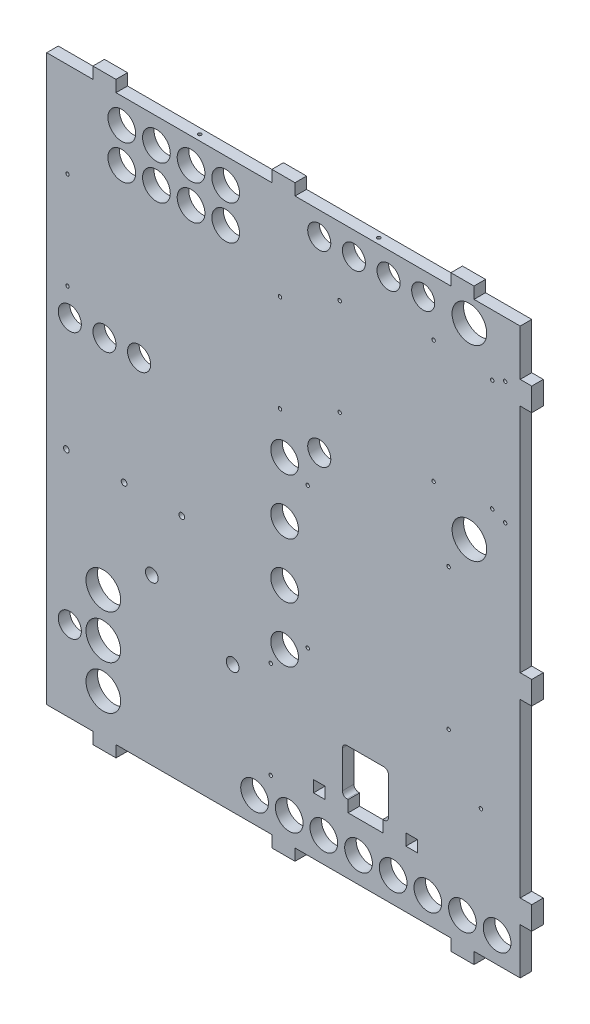
SolidWorks part; units mm, degrees
ref_plane "Ebene vorne" through (0, 0, 0) normal (0, 0, 1) x (1, 0, 0)
ref_plane "Ebene oben" through (0, 0, 0) normal (0, 1, 0) x (1, 0, 0)
ref_plane "Ebene rechts" through (0, 0, 0) normal (1, 0, 0) x (0, 0, -1)
sketch "Skizze1" plane through (0, 0, 0) normal (0, 0, 1) x (1, 0, 0)
  line L0 (0, 0) -> (0, -83406.5938) construction
  line L1 (0, 0) -> (83406.5938, 0) construction
  line L2 (55, 67.225) -> (75, 67.225)
  line L3 (-100, -67.225) -> (100, -67.225)
  line L4 (10.5, -37.555) -> (10.5, -42.555)
  line L5 (-100, 67.225) -> (-85, 67.225)
  line L6 (50.5, -37.555) -> (55.5, -37.555)
  line L7 (-100, -67.225) -> (100, 67.225) construction
  line L8 (-100, 67.225) -> (100, -67.225) construction
  line L9 (100, 47.225) -> (100, 67.225)
  line L10 (75, 67.225) -> (75, 72.225)
  line L11 (75, 72.225) -> (85, 72.225)
  line L12 (85, 67.225) -> (85, 72.225)
  line L13 (85, 67.225) -> (100, 67.225)
  line L14 (45, 67.225) -> (45, 72.225)
  line L15 (45, 72.225) -> (55, 72.225)
  line L16 (55, 67.225) -> (55, 72.225)
  line L17 (50.5, -37.555) -> (50.5, -42.555)
  line L18 (50.5, -42.555) -> (55.5, -42.555)
  line L19 (55.5, -37.555) -> (55.5, -42.555)
  line L20 (15.5, -42.555) -> (10.5, -42.555)
  line L21 (100, 47.225) -> (105, 47.225)
  line L22 (15.5, -37.555) -> (15.5, -42.555)
  line L23 (100, 37.225) -> (105, 37.225)
  line L24 (105, 47.225) -> (105, 37.225)
  line L25 (15.5, -37.555) -> (10.5, -37.555)
  line L26 (-75, 67.225) -> (45, 67.225)
  line L27 (100, -47.225) -> (100, -67.225)
  line L29 (-75, 67.225) -> (-75, 72.225)
  line L30 (-75, 72.225) -> (-85, 72.225)
  line L31 (105, -47.225) -> (105, -37.225)
  line L32 (100, -37.225) -> (105, -37.225)
  line L33 (-85, 67.225) -> (-85, 72.225)
  line L34 (100, -47.225) -> (105, -47.225)
  line L38 (100, 37.225) -> (100, -37.225)
  line L44 (-100, 37.225) -> (-100, -37.225)
  line L48 (-100, -47.225) -> (-105, -47.225)
  line L50 (-100, -37.225) -> (-105, -37.225)
  line L51 (-105, -47.225) -> (-105, -37.225)
  line L53 (-100, -47.225) -> (-100, -67.225)
  line L55 (-105, 47.225) -> (-105, 37.225)
  line L56 (-100, 37.225) -> (-105, 37.225)
  line L58 (-100, 47.225) -> (-105, 47.225)
  line L62 (-100, 47.225) -> (-100, 67.225)
  line L63 (33, -37.555) -> (33, -42.555) construction
  line L64 (25.5, -37.555) -> (40.5, -37.555)
  line L65 (25.5, -37.555) -> (25.5, -42.555)
  line L66 (25.5, -42.555) -> (40.5, -42.555)
  line L67 (40.5, -37.555) -> (40.5, -42.555)
  line L68 (105, 0) -> (105, -50000) construction
  point P5 (0, 0)
  dimension "D1" = 134.45
  dimension "D2" = 200
  dimension "D3" = 10
  dimension "D4" = 20
  dimension "D5" = 5
  dimension "D6" = 20
  dimension "D7" = 20
  dimension "D8" = 29.67
  dimension "D9" = 72
  dimension "D10" = 15
  dimension "D11" = 105
  dimension "D12" = 10
  dimension "D13" = 5
  dimension "D14" = 15
extrude "Aufsatz-Linear austragen1" add sketch "Skizze1" along normal blind 5
sketch "Skizze2" plane through (0, 0, 5) normal (0, 0, 1) x (1, 0, 0)
  line L0 (-42, 48.7841) -> (-42, -49951.2159) construction
  line L1 (-80.5107, -3.925) -> (49919.4893, -3.925) construction
  line L2 (-100, 67.225) -> (-85, 67.225) construction
  line L4 (100, 37.225) -> (100, -37.225) construction
  circle A0 centre (-59.5, 4.075) radius 2.75
  circle A1 centre (-24.5, 4.075) radius 2.75 construction
  circle A2 centre (-59.5, -11.925) radius 2.75 construction
  circle A3 centre (-24.5, -11.925) radius 2.75
  dimension "D1" = 5.5
  dimension "D2" = 63.15
  dimension "D3" = 142
  dimension "D4" = 35
  dimension "D5" = 16
extrude "Schnitt-Linear austragen1" cut sketch "Skizze2" against normal through all
sketch "Skizze3" plane through (0, 0, 5) normal (0, 0, 1) x (1, 0, 0)
  line L0 (33, -42.555) -> (33, -17.555) construction
  line L1 (25, -17.555) -> (41, -17.555)
  line L2 (23, -19.555) -> (23, -35.555)
  line L3 (37, -37.555) -> (41, -37.555)
  line L4 (43, -19.555) -> (43, -35.555)
  line L5 (-14.5, -32.225) -> (4.5, -32.225) construction
  line L6 (-17.5, -35.225) -> (-17.5, -54.225) construction
  line L7 (-14.5, -57.225) -> (4.5, -57.225) construction
  line L8 (7.5, -35.225) -> (7.5, -54.225) construction
  line L9 (25.5, -42.555) -> (40.5, -42.555) construction
  line L10 (25.5, -37.555) -> (40.5, -37.555) construction
  line L11 (29, -37.555) -> (25, -37.555)
  line L12 (-66.5, 54.225) -> (-66.5, 35.225)
  line L13 (37, -37.555) -> (29, -37.555)
  line L14 (-5, -32.225) -> (-5, -50032.225) construction
  line L17 (-88.5, 32.225) -> (-69.5, 32.225)
  line L18 (-100, -67.225) -> (100, -67.225) construction
  line L19 (-5, 57.225) -> (49995, 57.225) construction
  line L20 (-100, 67.225) -> (-85, 67.225) construction
  line L21 (-42, 57.225) -> (-42, -49942.775) construction
  line L24 (4.5, 57.225) -> (-14.5, 57.225)
  line L25 (7.5, 54.225) -> (7.5, 35.225)
  line L26 (4.5, 32.225) -> (-14.5, 32.225)
  line L27 (-17.5, 54.225) -> (-17.5, 35.225)
  line L28 (-91.5, 54.225) -> (-91.5, 35.225)
  line L29 (-88.5, 57.225) -> (-69.5, 57.225)
  line L30 (-79, 57.225) -> (-79, -49942.775) construction
  line L31 (-5, 22.3625) -> (49995, 22.3625) construction
  line L32 (4.5, -12.5) -> (-14.5, -12.5) construction
  line L33 (-17.5, -9.5) -> (-17.5, 9.5) construction
  line L34 (4.5, 12.5) -> (-14.5, 12.5) construction
  line L35 (7.5, -9.5) -> (7.5, 9.5) construction
  line L36 (4.5, 32.225) -> (4.5, 12.5) construction
  line L37 (4.5, -12.5) -> (4.5, -32.225) construction
  line L38 (4.5, -32.225) -> (4.5, -12.5) construction
  circle A0 centre (-24.5, -11.925) radius 2.75 construction
  arc A1 (23, -35.555) -> (25, -37.555) centre (25, -35.555) ccw
  arc A2 (43, -35.555) -> (41, -37.555) centre (41, -35.555) cw
  arc A3 (43, -19.555) -> (41, -17.555) centre (41, -19.555) ccw
  arc A4 (25, -17.555) -> (23, -19.555) centre (25, -19.555) ccw
  arc A5 (-17.5, -54.225) -> (-14.5, -57.225) centre (-14.5, -54.225) ccw construction
  arc A6 (7.5, -54.225) -> (4.5, -57.225) centre (4.5, -54.225) cw construction
  arc A8 (7.5, -35.225) -> (4.5, -32.225) centre (4.5, -35.225) ccw construction
  arc A9 (-14.5, -32.225) -> (-17.5, -35.225) centre (-14.5, -35.225) ccw construction
  arc A10 (7.5, 35.225) -> (4.5, 32.225) centre (4.5, 35.225) cw
  arc A11 (-14.5, 32.225) -> (-17.5, 35.225) centre (-14.5, 35.225) cw
  arc A12 (-17.5, 54.225) -> (-14.5, 57.225) centre (-14.5, 54.225) cw
  arc A14 (4.5, 57.225) -> (7.5, 54.225) centre (4.5, 54.225) cw
  arc A15 (-88.5, 57.225) -> (-91.5, 54.225) centre (-88.5, 54.225) ccw
  arc A16 (-66.5, 54.225) -> (-69.5, 57.225) centre (-69.5, 54.225) ccw
  arc A17 (-69.5, 32.225) -> (-66.5, 35.225) centre (-69.5, 35.225) ccw
  arc A18 (-91.5, 35.225) -> (-88.5, 32.225) centre (-88.5, 35.225) ccw
  circle A19 centre (-59.5, 4.075) radius 2.75 construction
  arc A20 (-17.5, -9.5) -> (-14.5, -12.5) centre (-14.5, -9.5) ccw construction
  arc A21 (-14.5, 12.5) -> (-17.5, 9.5) centre (-14.5, 9.5) ccw construction
  arc A22 (7.5, 9.5) -> (4.5, 12.5) centre (4.5, 9.5) ccw construction
  arc A23 (4.5, -12.5) -> (7.5, -9.5) centre (4.5, -9.5) ccw construction
  point P19 (23, -37.555)
  point P22 (43, -37.555)
  point P25 (43, -17.555)
  point P28 (23, -17.555)
  point P52 (43, -37.555)
  point P53 (-5, -32.225)
  point P67 (-17.5, 32.225)
  point P70 (-17.5, 57.225)
  point P73 (7.5, 57.225)
  point P86 (-91.5, 57.225)
  point P87 (-66.5, 57.225)
  point P88 (-66.5, 32.225)
  point P91 (-79, 57.225)
  dimension "D1" = 20
  dimension "D2" = 20
  dimension "D6" = 25
  dimension "D3" = 2
  dimension "D7" = 3
  dimension "D12" = 25
  dimension "D5" = 19.5
  dimension "D15" = 2
  dimension "D17" = 3
  dimension "D18" = 19.5
  dimension "D4" = 10
  dimension "D8" = 25
  dimension "D9" = 25
  dimension "D11" = 10
  dimension "D13" = 0
  dimension "D14" = 8
extrude "Schnitt-Linear austragen2" cut sketch "Skizze3" against normal through all
sketch "Skizze4" plane through (0, 0, 5) normal (0, 0, 1) x (1, 0, 0)
  line L0 (55, 67.225) -> (75, 67.225) construction
  line L1 (100, 47.225) -> (100, 67.225) construction
  line L2 (-100, -67.225) -> (100, -67.225) construction
  line L3 (-80.5, -30.925) -> (49919.5, -30.925) construction
  line L4 (-80.5, -30.925) -> (-80.5, -50030.925) construction
  circle A0 centre (45.5, 53.325) radius 7.5 construction
  circle A1 centre (-80.5, -30.925) radius 7.5
  circle A2 centre (-59.5, 4.075) radius 2.75 construction
  circle A3 centre (-80.5, -11.925) radius 7.5
  circle A4 centre (-80.5, -49.925) radius 7.5
  dimension "D1" = 13.9
  dimension "D3" = 15
  dimension "D5" = 21
  dimension "D6" = 19
  dimension "D2" = 54.5
  dimension "D4" = 36.3
extrude "Schnitt-Linear austragen3" cut sketch "Skizze4" against normal through all
sketch "Skizze5" plane through (0, 0, 5) normal (0, 0, 1) x (1, 0, 0)
  line L0 (-8, -45.225) -> (-8, -3.225) construction
  line L1 (83, -12.225) -> (-8, -12.225) construction
  line L2 (-100, -67.225) -> (100, -67.225) construction
  line L3 (100, 37.225) -> (100, -37.225) construction
  line L4 (-30.2483, -49.225) -> (49969.7517, -49.225) construction
  line L5 (-17.9531, -56.225) -> (49982.0469, -56.225) construction
  line L6 (22.5, -56.9878) -> (22.5, -50056.9878) construction
  line L7 (37.5, -10.225) -> (37.5, -50010.225) construction
  circle A0 centre (-8, -45.225) radius 0.75
  circle A1 centre (-8, -3.225) radius 0.75
  circle A2 centre (83, -12.225) radius 0.75
  circle A3 centre (-15, -56.225) radius 6
  circle A4 centre (0, -56.225) radius 6
  circle A5 centre (15, -56.225) radius 6
  circle A6 centre (30, -56.225) radius 6
  circle A7 centre (45, -56.225) radius 6
  circle A8 centre (60, -56.225) radius 6
  circle A9 centre (75, -56.225) radius 6
  circle A10 centre (90, -56.225) radius 6
  point P33 (0, 0)
  point P36 (37.5, -12.225)
  dimension "D1" = 1.5
  dimension "D9" = 12
  dimension "D2" = 42
  dimension "D4" = 91
  dimension "D3" = 9
  dimension "D5" = 22
  dimension "D6" = 17
  dimension "D7" = 4
  dimension "D10" = 7
  dimension "D11" = 15
  dimension "D8" = 8
extrude "Sensors" cut sketch "Skizze5" against normal through all
sketch "Skizze6" plane through (0, 0, 0) normal (0, 0, -1) x (-1, 0, 0)
  line L0 (100, -67.225) -> (-100, -67.225) construction
  line L1 (160, 47.225) -> (160, 37.225)
  line L2 (100, 67.225) -> (100, -67.225)
  line L3 (100, -67.225) -> (160, -67.225)
  line L4 (160, 67.225) -> (160, 47.225)
  line L6 (100, -37.225) -> (105, -37.225) construction
  line L7 (160, -47.225) -> (160, -67.225)
  line L8 (100, -47.225) -> (105, -47.225) construction
  line L9 (100, 47.225) -> (105, 47.225) construction
  line L10 (100, 37.225) -> (105, 37.225) construction
  line L11 (75, 67.225) -> (-45, 67.225) construction
  line L17 (160, 37.225) -> (160, -37.225)
  line L18 (-30.5, 67.225) -> (100, 67.225)
  line L19 (-30.5, 67.225) -> (-30.5, 177.225)
  line L20 (-30.5, 177.225) -> (160, 177.225)
  line L21 (160, 67.225) -> (160, 177.225)
  line L22 (-100, 47.225) -> (-100, 67.225) construction
  line L23 (160, -37.225) -> (160, -47.225)
  dimension "D1" = 60
  dimension "D2" = 110
  dimension "D3" = 69.5
extrude "Aufsatz-Linear austragen2" add sketch "Skizze6" against normal blind 5
sketch "Skizze7" plane through (0, 0, 0) normal (0, 0, -1) x (-1, 0, 0)
  line L0 (71.5, 32.775) -> (96.5, 32.775) construction
  line L1 (160, -67.225) -> (-100, -67.225) construction
  line L4 (91.5, 54.225) -> (91.5, 35.225) construction
  line L5 (46.5, 32.775) -> (71.5, 32.775) construction
  line L6 (122.7956, 60.525) -> (50122.7956, 60.525) construction
  circle A0 centre (71.5, 32.775) radius 1.25
  circle A1 centre (96.5, 32.775) radius 1.25
  circle A4 centre (46.5, 32.775) radius 1.25
  dimension "D3" = 2.5
  dimension "D1" = 100
  dimension "D2" = 25
  dimension "D4" = 20
extrude "Schnitt-Linear austragen5" cut sketch "Skizze7" against normal through all
sketch "Sketch1" plane through (0, 0, 5) normal (0, 0, 1) x (1, 0, 0)
  line L1 (30.5, 177.225) -> (100, 177.225)
  line L2 (30.5, 177.225) -> (30.5, 67.225)
  line L3 (30.5, 67.225) -> (100, 67.225)
  line L4 (100, 177.225) -> (100, 67.225)
extrude "Boss-Extrude1" add sketch "Sketch1" against normal blind 5
sketch "Skizze9" plane through (0, 0, 5) normal (0, 0, 1) x (1, 0, 0)
  line L0 (-33.1526, 41.015) -> (49966.8474, 41.015) construction
  line L1 (38.5, 36.3664) -> (38.5, 48631.464) construction
  line L5 (-2, 7.1234) -> (-2, 89.5656) construction
  line L7 (-17.5, 54.225) -> (-17.5, 35.225) construction
  line L8 (4.5, 57.225) -> (-14.5, 57.225) construction
  circle A0 centre (8, 71.515) radius 0.75
  circle A1 centre (69, 71.515) radius 0.75
  circle A2 centre (8, 10.515) radius 0.75
  circle A3 centre (69, 10.515) radius 0.75
  circle A4 centre (-2, 5.015) radius 6
  circle A5 centre (-2, 29.015) radius 6
  circle A6 centre (-2, 53.015) radius 6
  circle A7 centre (-2, 77.015) radius 6
  point P13 (0, 0)
  point P16 (0, 0)
  point P29 (0, 0)
  dimension "D1" = 1.5
  dimension "D8" = 12
  dimension "D2" = 61
  dimension "D3" = 61
  dimension "D7" = 24
  dimension "D5" = 15.5
  dimension "D9" = 4.21
  dimension "D4" = 10
  dimension "D6" = 4
extrude "DiscreteChannel" cut sketch "Skizze9" against normal through all
sketch "Skizze10" plane through (0, 0, 5) normal (0, 0, 1) x (1, 0, 0)
  line L0 (-50, 127.2474) -> (-50, -49872.7526) construction
  line L1 (-69.94, 115.225) -> (49930.06, 115.225) construction
  line L4 (-50.8687, 166.225) -> (49949.1313, 166.225) construction
  line L5 (-75.5, 136.225) -> (49924.5, 136.225) construction
  line L6 (-72.5, 172.225) -> (-27.5, 172.225) construction
  line L7 (-72.5, 166.225) -> (-72.5, 151.225) construction
  line L8 (-160, 177.225) -> (100, 177.225) construction
  line L9 (100, 47.225) -> (100, 177.225) construction
  circle A0 centre (-4, 136.225) radius 0.75
  circle A1 centre (-4, 94.225) radius 0.75
  circle A2 centre (-96, 136.225) radius 0.75
  circle A3 centre (-96, 94.225) radius 0.75
  circle A4 centre (-72.5, 166.225) radius 6
  circle A5 centre (-2, 5.015) radius 6 construction
  circle A6 centre (-57.5, 166.225) radius 6
  circle A7 centre (-42.5, 166.225) radius 6
  circle A8 centre (-27.5, 166.225) radius 6
  circle A9 centre (-27.5, 151.225) radius 6
  circle A10 centre (-42.5, 151.225) radius 6
  circle A11 centre (-57.5, 151.225) radius 6
  circle A12 centre (-72.5, 151.225) radius 6
  point P20 (-50, 172.225)
  point P29 (45.295, 151.225)
  dimension "D6" = 4
  dimension "D5" = 1.5
  dimension "D1" = 42
  dimension "D2" = 92
  dimension "D7" = 15
  dimension "D9" = 30
  dimension "D8" = 15
  dimension "D4" = 11
  dimension "D10" = 150
  dimension "D3" = 2
extrude "ContChannel" cut sketch "Skizze10" against normal through all
sketch "Sketch2" plane through (0, 0, 5) normal (0, 0, 1) x (1, 0, 0)
  line L0 (-14.5, 32.225) -> (-7.0691, 32.225) construction
  line L1 (3.0691, 32.225) -> (4.5, 32.225) construction
  line L2 (7.5, 35.225) -> (7.5, 54.225) construction
  line L3 (4.5, 57.225) -> (2.275, 57.225) construction
  line L4 (-6.275, 57.225) -> (-14.5, 57.225) construction
  line L5 (-17.5, 54.225) -> (-17.5, 35.225) construction
  line L6 (-14.5, 32.225) -> (-7.0691, 32.225)
  line L7 (3.0691, 32.225) -> (4.5, 32.225)
  line L8 (7.5, 35.225) -> (7.5, 54.225)
  line L9 (4.5, 57.225) -> (2.275, 57.225)
  line L10 (-6.275, 57.225) -> (-14.5, 57.225)
  line L11 (-17.5, 54.225) -> (-17.5, 35.225)
  arc A0 (-17.5, 35.225) -> (-14.5, 32.225) centre (-14.5, 35.225) ccw construction
  arc A1 (-7.0691, 32.225) -> (3.0691, 32.225) centre (-2, 29.015) ccw construction
  arc A2 (4.5, 32.225) -> (7.5, 35.225) centre (4.5, 35.225) ccw construction
  arc A3 (7.5, 54.225) -> (4.5, 57.225) centre (4.5, 54.225) ccw construction
  arc A4 (2.275, 57.225) -> (-6.275, 57.225) centre (-2, 53.015) ccw construction
  arc A5 (-14.5, 57.225) -> (-17.5, 54.225) centre (-14.5, 54.225) ccw construction
  arc A6 (-17.5, 35.225) -> (-14.5, 32.225) centre (-14.5, 35.225) ccw
  arc A7 (-7.0691, 32.225) -> (3.0691, 32.225) centre (-2, 29.015) ccw construction
  arc A8 (4.5, 32.225) -> (7.5, 35.225) centre (4.5, 35.225) ccw
  arc A9 (7.5, 54.225) -> (4.5, 57.225) centre (4.5, 54.225) ccw
  arc A10 (2.275, 57.225) -> (-6.275, 57.225) centre (-2, 53.015) ccw construction
  arc A11 (-14.5, 57.225) -> (-17.5, 54.225) centre (-14.5, 54.225) ccw
  arc A12 (-7.0691, 32.225) -> (3.0691, 32.225) centre (-2, 29.015) cw
  arc A13 (-6.275, 57.225) -> (2.275, 57.225) centre (-2, 53.015) ccw
  point P20 (2.6378, 56.8217)
extrude "Boss-Extrude2" add sketch "Sketch2" against normal blind 5
sketch "Skizze8" plane through (0, 0, 5) normal (0, 0, 1) x (1, 0, 0)
  line L0 (-165.5788, 126.725) -> (49834.4212, 126.725) construction
  line L1 (78, 176.1292) -> (78, 50176.1292) construction
  line L2 (-160, 177.225) -> (100, 177.225) construction
  line L3 (100, 47.225) -> (100, 177.225) construction
  line L5 (62.5, 100.225) -> (93.5, 100.225) construction
  circle A0 centre (62.5, 153.225) radius 0.75
  circle A1 centre (93.5, 153.225) radius 0.75
  circle A2 centre (62.5, 100.225) radius 0.75
  circle A3 centre (93.5, 100.225) radius 0.75
  circle A4 centre (78, 86.225) radius 7.5
  circle A5 centre (-80.5, -11.925) radius 7.5 construction
  circle A6 centre (78, 167.225) radius 7.5
  dimension "D1" = 1.5
  dimension "D2" = 53
  dimension "D3" = 31
  dimension "D4" = 14
  dimension "D5" = 10
  dimension "D6" = 6.5
extrude "StepDownConverter" cut sketch "Skizze8" against normal through all
sketch "Sketch3" plane through (0, 0, 5) normal (0, 0, 1) x (1, 0, 0)
  line L0 (46.6666, 126.725) -> (50046.6666, 126.725) construction
  line L1 (100, 47.225) -> (100, 177.225) construction
  line L2 (93.5, 153.225) -> (93.5, 100.225) construction
  line L3 (78, 167.225) -> (50078, 167.225) construction
  circle A0 centre (21.85, 147.68) radius 0.75
  circle A1 centre (87.89, 102.59) radius 0.75
  circle A2 centre (87.89, 150.86) radius 0.75
  circle A3 centre (21.85, 105.77) radius 0.75
  circle A4 centre (13, 167.225) radius 5
  circle A5 centre (28, 167.225) radius 5
  circle A6 centre (43, 167.225) radius 5
  circle A7 centre (58, 167.225) radius 5
  circle A8 centre (78, 167.225) radius 7.5 construction
  circle A9 centre (13, 86.225) radius 5
  point P10 (93.5, 126.725)
  point P28 (0, 0)
  point P29 (6.1817, 167.225)
  dimension "D4" = 1.5
  dimension "D6" = 10
  dimension "D1" = 66.04
  dimension "D2" = 41.91
  dimension "D3" = 3.18
  dimension "D5" = 12.11
  dimension "D8" = 15
  dimension "D9" = 20
  dimension "D7" = 4
extrude "BBB" cut sketch "Sketch3" against normal blind 5
sketch "Sketch4" plane through (0, 0, 5) normal (0, 0, 1) x (1, 0, 0)
  line L0 (-88.5, 32.225) -> (-72.6225, 32.225) construction
  line L1 (-70.3775, 32.225) -> (-69.5, 32.225) construction
  line L2 (-66.5, 35.225) -> (-66.5, 54.225) construction
  line L3 (-69.5, 57.225) -> (-88.5, 57.225) construction
  line L4 (-91.5, 54.225) -> (-91.5, 35.225) construction
  line L5 (-88.5, 32.225) -> (-72.6225, 32.225)
  line L6 (-70.3775, 32.225) -> (-69.5, 32.225)
  line L7 (-66.5, 35.225) -> (-66.5, 54.225)
  line L8 (-69.5, 57.225) -> (-88.5, 57.225)
  line L9 (-91.5, 54.225) -> (-91.5, 35.225)
  arc A0 (-91.5, 35.225) -> (-88.5, 32.225) centre (-88.5, 35.225) ccw construction
  arc A1 (-72.6225, 32.225) -> (-70.3775, 32.225) centre (-71.5, 32.775) ccw construction
  arc A2 (-69.5, 32.225) -> (-66.5, 35.225) centre (-69.5, 35.225) ccw construction
  arc A3 (-66.5, 54.225) -> (-69.5, 57.225) centre (-69.5, 54.225) ccw construction
  arc A4 (-88.5, 57.225) -> (-91.5, 54.225) centre (-88.5, 54.225) ccw construction
  arc A5 (-91.5, 35.225) -> (-88.5, 32.225) centre (-88.5, 35.225) ccw
  arc A6 (-72.6225, 32.225) -> (-70.3775, 32.225) centre (-71.5, 32.775) ccw construction
  arc A7 (-69.5, 32.225) -> (-66.5, 35.225) centre (-69.5, 35.225) ccw
  arc A8 (-66.5, 54.225) -> (-69.5, 57.225) centre (-69.5, 54.225) ccw
  arc A9 (-88.5, 57.225) -> (-91.5, 54.225) centre (-88.5, 54.225) ccw
  arc A10 (-72.6225, 32.225) -> (-70.3775, 32.225) centre (-71.5, 32.775) cw
  point P16 (0, 0)
extrude "Boss-Extrude3" add sketch "Sketch4" against normal blind 5
sketch "Sketch5" plane through (0, 0, 5) normal (0, 0, 1) x (1, 0, 0)
  line L0 (-160, -67.225) -> (100, -67.225) construction
  line L1 (-160, 177.225) -> (-105, 177.225)
  line L2 (-160, 177.225) -> (-160, -67.225)
  line L3 (-160, -67.225) -> (-105, -67.225)
  line L4 (-105, 177.225) -> (-105, -67.225)
  line L5 (100, 47.225) -> (100, 177.225) construction
  dimension "D1" = 205
extrude "Cut-Extrude2" cut sketch "Sketch5" against normal blind 5
sketch "Sketch6" plane through (0, 0, 5) normal (0, 0, 1) x (1, 0, 0)
  line L0 (-105, 82.775) -> (49895, 82.775) construction
  line L2 (-105, -67.225) -> (-105, 177.225) construction
  line L3 (-95, 82.775) -> (-95, -49917.225) construction
  circle A0 centre (-96.5, 32.775) radius 1.25 construction
  circle A1 centre (-95, 82.775) radius 5
  circle A2 centre (-80, 82.775) radius 5
  circle A3 centre (-95, -32.225) radius 5
  circle A4 centre (-65, 82.775) radius 5
  dimension "D2" = 10
  dimension "D1" = 50
  dimension "D4" = 10
  dimension "D5" = 15
  dimension "D6" = 115
  dimension "D3" = 3
extrude "Cut-Extrude3" cut sketch "Sketch6" against normal blind 5
sketch "Sketch7" plane through (0, 0, 5) normal (0, 0, 1) x (1, 0, 0)
  line L0 (100, 47.225) -> (100, 177.225) construction
  line L1 (100, 157.225) -> (105, 157.225)
  line L2 (100, 157.225) -> (100, 147.225)
  line L3 (100, 147.225) -> (105, 147.225)
  line L4 (105, 157.225) -> (105, 147.225)
  line L5 (100, -37.225) -> (105, -37.225) construction
  line L6 (-105, 177.225) -> (100, 177.225) construction
  dimension "D1" = 10
  dimension "D2" = 20
extrude "Boss-Extrude4" add sketch "Sketch7" against normal blind 5
sketch "Sketch8" plane through (0, 0, 5) normal (0, 0, 1) x (1, 0, 0)
  line L0 (-105, -67.225) -> (100, -67.225) construction
  line L1 (-85, -67.225) -> (-75, -67.225)
  line L2 (-85, -67.225) -> (-85, -72.225)
  line L3 (-85, -72.225) -> (-75, -72.225)
  line L4 (-75, -67.225) -> (-75, -72.225)
  line L5 (-75, -67.225) -> (70, -67.225) construction
  line L6 (-7.5, -67.225) -> (2.5, -67.225)
  line L7 (-7.5, -67.225) -> (-7.5, -72.225)
  line L8 (-7.5, -72.225) -> (2.5, -72.225)
  line L9 (2.5, -67.225) -> (2.5, -72.225)
  line L10 (70, -67.225) -> (80, -67.225)
  line L11 (70, -67.225) -> (70, -72.225)
  line L12 (70, -72.225) -> (80, -72.225)
  line L13 (80, -67.225) -> (80, -72.225)
  line L14 (-2.5, -67.225) -> (-2.5, -106.7893) construction
  line L15 (-105, -67.225) -> (-105, 177.225) construction
  line L16 (100, -47.225) -> (100, -67.225) construction
  line L17 (-105, 55) -> (49895, 55) construction
  line L18 (70, 182.225) -> (80, 182.225)
  line L19 (80, 177.225) -> (80, 182.225)
  line L20 (70, 177.225) -> (80, 177.225)
  line L21 (70, 177.225) -> (70, 182.225)
  line L22 (-7.5, 182.225) -> (2.5, 182.225)
  line L23 (-7.5, 177.225) -> (2.5, 177.225)
  line L24 (-7.5, 177.225) -> (-7.5, 182.225)
  line L25 (-85, 177.225) -> (-75, 177.225)
  line L26 (-75, 177.225) -> (-75, 182.225)
  line L27 (-85, 182.225) -> (-75, 182.225)
  line L28 (-85, 177.225) -> (-85, 182.225)
  line L29 (2.5, 177.225) -> (2.5, 182.225)
  point P22 (-105, 55)
  dimension "D1" = 5
  dimension "D2" = 10
  dimension "D3" = 20
  dimension "D4" = 20
extrude "Boss-Extrude5" add sketch "Sketch8" against normal blind 5
sketch "Sketch10" plane through (0, 177.225, 0) normal (0, 1, 0) x (1, 0, 0)
  line L0 (-75, -2.5) -> (-7.5, -2.5) construction
  line L1 (-75, 0) -> (-75, -5) construction
  line L2 (-7.5, 0) -> (-7.5, -5) construction
  line L3 (-7.5, -2.5) -> (2.5, -2.5) construction
  line L4 (2.5, 0) -> (2.5, -5) construction
  line L5 (2.5, -2.5) -> (70, -2.5) construction
  line L6 (70, 0) -> (70, -5) construction
  circle A0 centre (36.25, -2.5) radius 0.75
  circle A1 centre (-41.25, -2.5) radius 0.75
  dimension "D1" = 1.5
extrude "Cut-Extrude4" cut sketch "Sketch10" against normal blind 10
ref_plane "Plane1" through (0, 55, 0) normal (0, 1, 0) x (1, 0, 0)
mirror "Mirror1" about plane through (0, 55, 0) normal (0, 1, 0) of "Cut-Extrude4"
equation "\"m3-gewinde\"= 1.5"
equation "\"m3-durchgang\"= 2.5"
equation "\"D1@Skizze5\"=\"m3-gewinde\""
equation "\"stecker-durchgang\"= 12"
equation "\"D9@Skizze5\"=\"stecker-durchgang\""
equation "\"D3@Skizze7\"=\"m3-durchgang\""
equation "\"D1@Skizze8\"=\"m3-gewinde\""
equation "\"D1@Skizze9\"=\"m3-gewinde\""
equation "\"D8@Skizze9\"=\"stecker-durchgang\""
equation "\"D5@Skizze10\"=\"m3-gewinde\""
